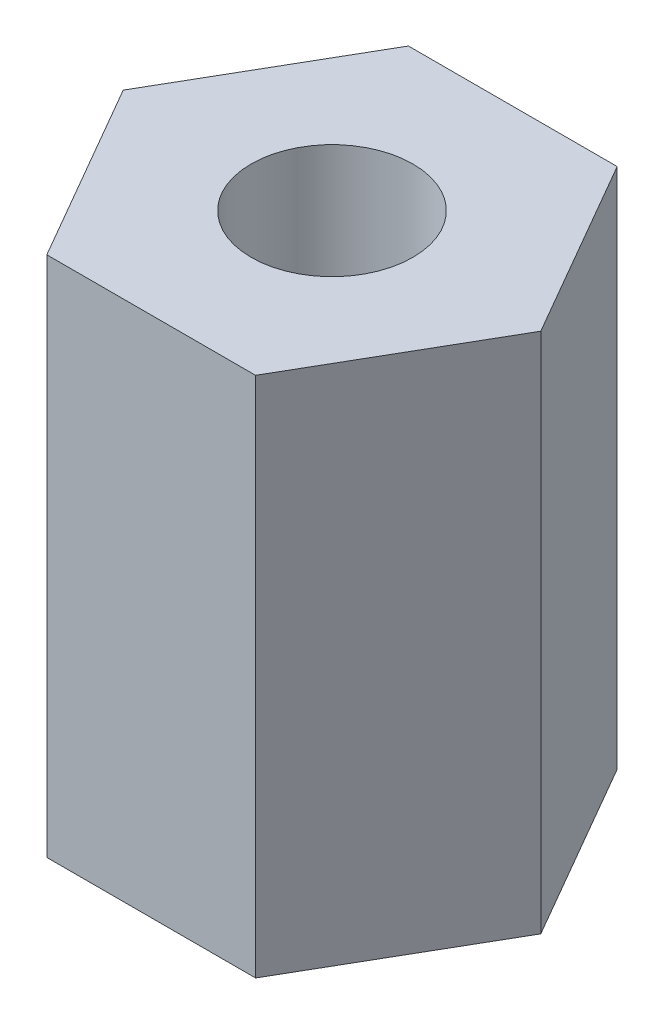
SolidWorks part; units mm, degrees
ref_plane "前基準面" through (0, 0, 0) normal (0, 0, 1) x (1, 0, 0)
ref_plane "上基準面" through (0, 0, 0) normal (0, 1, 0) x (1, 0, 0)
ref_plane "右基準面" through (0, 0, 0) normal (1, 0, 0) x (0, 0, -1)
sketch "草圖1" plane through (0, 0, 0) normal (0, 1, 0) x (1, 0, 0)
  line L1 (2, 3.4641) -> (-2, 3.4641)
  line L2 (-2, 3.4641) -> (-4, 0)
  line L3 (-4, 0) -> (-2, -3.4641)
  line L4 (-2, -3.4641) -> (2, -3.4641)
  line L5 (2, -3.4641) -> (4, 0)
  line L6 (4, 0) -> (2, 3.4641)
  circle A0 centre (0, 0) radius 3.4641 construction
  circle A1 centre (0, 0) radius 1.55
  dimension "D1" = 3.1
  dimension "D2" = 4
extrude "填料-伸長1" add sketch "草圖1" along normal blind 10 contours A1 | L1 L2 L3 L4 L5 L6
